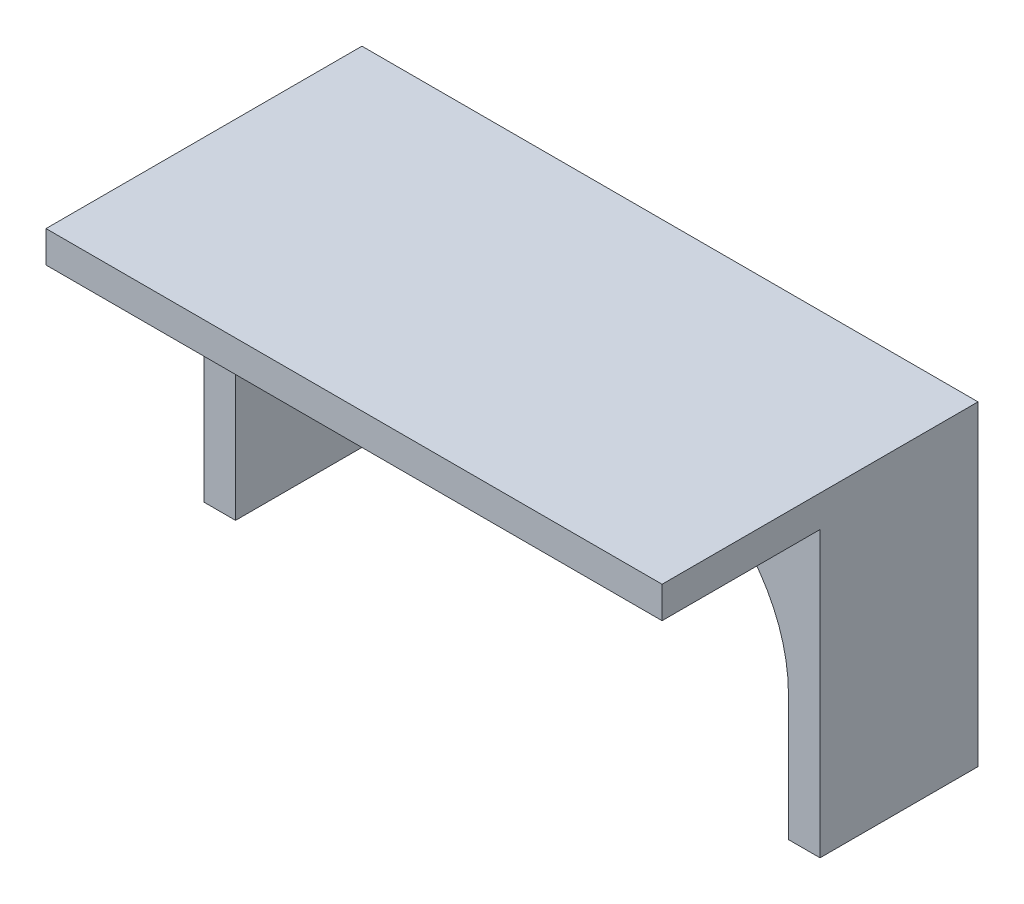
SolidWorks part; units mm, degrees
ref_plane "Front Plane" through (0, 0, 0) normal (0, 0, 1) x (1, 0, 0)
ref_plane "Top Plane" through (0, 0, 0) normal (0, 1, 0) x (1, 0, 0)
ref_plane "Right Plane" through (0, 0, 0) normal (1, 0, 0) x (0, 0, -1)
sketch "Sketch1" plane through (0, 0, 0) normal (0, 0, 1) x (1, 0, 0)
  line L0 (-78.7738, 0) -> (78.7738, 0)
  line L1 (-19.5, 20) -> (19.5, 20)
  line L2 (-19.5, 20) -> (-19.5, -20)
  line L3 (-19.5, -20) -> (19.5, -20)
  line L4 (19.5, 20) -> (19.5, -20)
  line L5 (-19.5, 20) -> (19.5, -20) construction
  line L6 (-19.5, -20) -> (19.5, 20) construction
  line L7 (-7.5, 18) -> (7.5, 18)
  line L8 (-17.5, 8) -> (-17.5, -18)
  line L9 (-17.5, -18) -> (17.5, -18)
  line L10 (17.5, 8) -> (17.5, -18)
  line L11 (-17.5, 18) -> (17.5, -18) construction
  line L12 (-17.5, -18) -> (17.5, 18) construction
  arc A0 (7.5, 18) -> (17.5, 8) centre (7.5, 8) cw
  arc A1 (-7.5, 18) -> (-17.5, 8) centre (-7.5, 8) ccw
  point P0 (0, 0)
  point P6 (0, 0)
  point P14 (0, 0)
  dimension "D5" = 10
  dimension "D1" = 39
  dimension "D2" = 35
  dimension "D3" = 2
  dimension "D4" = 20
extrude "Boss-Extrude1" add sketch "Sketch1" along normal blind 10 contours L7 L10 L0 L4 L1 L2 L8
sketch "Sketch2" plane through (0, 0, 10) normal (0, 0, 1) x (1, 0, 0)
  line L0 (19.5, 20) -> (19.5, 0) construction
  line L1 (-19.5, 20) -> (19.5, 20)
  line L2 (-19.5, 20) -> (-19.5, 18)
  line L3 (-19.5, 18) -> (19.5, 18)
  line L4 (19.5, 20) -> (19.5, 18)
  dimension "D1" = 2
extrude "Boss-Extrude2" add sketch "Sketch2" along normal blind 10
